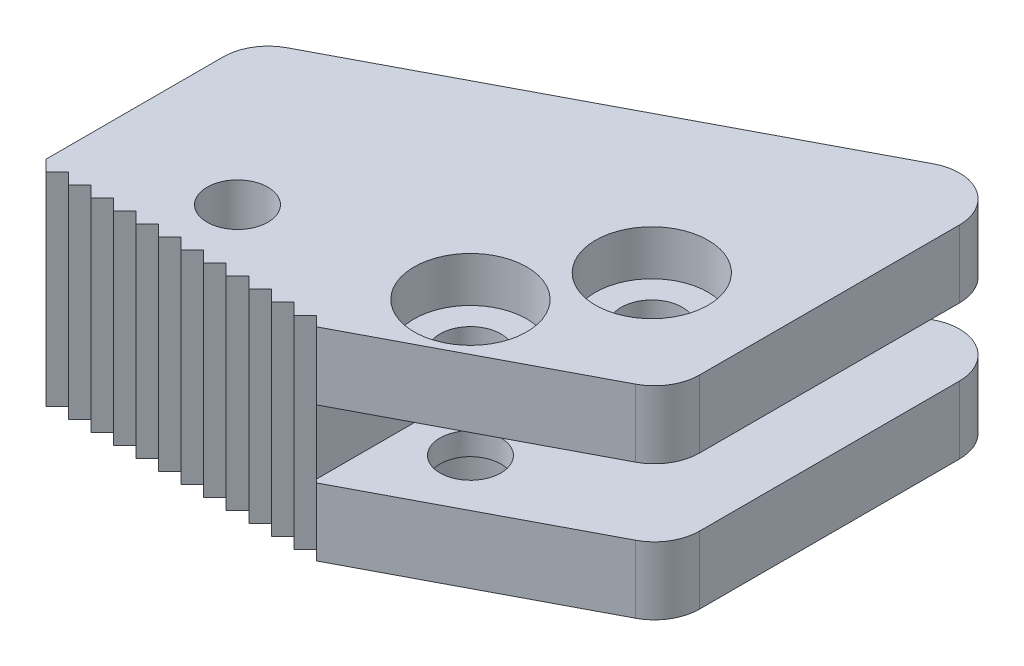
SolidWorks part; units mm, degrees
ref_plane "Alzado" through (0, 0, 0) normal (0, 0, 1) x (1, 0, 0)
ref_plane "Planta" through (0, 0, 0) normal (0, 1, 0) x (1, 0, 0)
ref_plane "Vista lateral" through (0, 0, 0) normal (1, 0, 0) x (0, 0, -1)
sketch "Sketch1" plane through (0, 0, 0) normal (0, 1, 0) x (1, 0, 0)
  line L2 (37.6026, 29.11) -> (37.6026, 11)
  line L3 (37.6026, 11) -> (16.67, 0)
  line L4 (16.67, 0) -> (0, 0)
  line L5 (0, 0) -> (0, 9.35)
  line L6 (0, 9.35) -> (37.6026, 29.11) construction
  line L7 (0, 9.35) -> (0, 15.35)
  line L8 (0, 15.35) -> (37.6026, 35.11)
  line L9 (37.6026, 35.11) -> (37.6026, 29.11)
  dimension "D1" = 9.35
  dimension "D2" = 11
  dimension "D3" = 16.67
  dimension "D4" = 18.11
  dimension "D5" = 6
extrude "Boss-Extrude1" add sketch "Sketch1" along normal blind 18
sketch "Sketch6" plane through (0, 18, 0) normal (0, 1, 0) x (1, 0, 0)
  line L0 (0, 0) -> (-8, 0)
  line L1 (-8, 0) -> (-8, 19.146)
  line L2 (-8, 19.146) -> (37.6026, 43.11)
  line L3 (37.6026, 43.11) -> (37.6026, 35.11)
  line L4 (37.6026, 35.11) -> (0, 15.35)
  line L5 (0, 15.35) -> (0, 0)
  line L6 (37.6026, 11) -> (37.6026, 35.11) construction
  dimension "D1" = 8
  dimension "D2" = 8
extrude "Boss-Extrude2" add sketch "Sketch6" against normal through all
sketch "Sketch2" plane through (0, 18, 0) normal (0, 1, 0) x (1, 0, 0)
  line L1 (-8, 0) -> (16.67, 0) construction
  circle A0 centre (4, 6) radius 2.7
  circle A1 centre (21.62, 9.06) radius 2.7
  circle A2 centre (27.62, 19.16) radius 2.7
  dimension "D1" = 4
  dimension "D3" = 5.4
  dimension "D2" = 6
  dimension "D4" = 6
  dimension "D5" = 10.1
  dimension "D6" = 4.95
  dimension "D7" = 9.06
extrude "Cut-Extrude1" cut sketch "Sketch2" against normal through all contours A0 | A1 | A2
sketch "Sketch3" plane through (0, 0, 0) normal (0, 0, 1) x (1, 0, 0)
  line L5 (37.6026, 18) -> (37.6026, 0) construction
  line L6 (37.6026, 6) -> (16.6026, 6)
  line L7 (37.6026, 6) -> (37.6026, 12)
  line L8 (37.6026, 12) -> (16.6026, 12)
  line L9 (16.6026, 6) -> (16.6026, 12)
  line L10 (37.6026, 6) -> (16.6026, 12) construction
  line L11 (37.6026, 12) -> (16.6026, 6) construction
  line L12 (37.6026, 0) -> (37.6026, 18) construction
  point P4 (27.1026, 9)
  point P12 (37.6026, 9)
  dimension "D1" = 6
  dimension "D2" = 21
extrude "Cut-Extrude2" cut sketch "Sketch3" against normal through all
sketch "Sketch4" plane through (0, 18, 0) normal (0, 1, 0) x (1, 0, 0)
  line L1 (-8, 0) -> (-8, 1)
  line L2 (-5, 0) -> (-4, 1)
  line L4 (-8, 19.146) -> (-8, 0) construction
  line L33 (-8, 1) -> (-7, 0)
  line L35 (-8, 0) -> (16.67, 0) construction
  line L36 (-7, 0) -> (-6, 1)
  line L38 (-4, 1) -> (-3, 0)
  line L39 (-6, 1) -> (-5, 0)
  line L40 (-8, 0) -> (-8, -0.2)
  line L41 (-8, -0.2) -> (16.67, -0.2)
  line L42 (16.67, -0.2) -> (16.67, 0)
  line L43 (-3, 0) -> (-2, 1)
  line L44 (-2, 1) -> (-1, 0)
  line L45 (-1, 0) -> (0, 1)
  line L46 (0, 1) -> (1, 0)
  line L47 (1, 0) -> (2, 1)
  line L48 (2, 1) -> (3, 0)
  line L49 (3, 0) -> (4, 1)
  line L50 (4, 1) -> (5, 0)
  line L51 (5, 0) -> (6, 1)
  line L52 (6, 1) -> (7, 0)
  line L53 (7, 0) -> (8, 1)
  line L54 (8, 1) -> (9, 0)
  line L55 (9, 0) -> (10, 1)
  line L56 (10, 1) -> (11, 0)
  line L57 (11, 0) -> (12, 1)
  line L58 (12, 1) -> (13, 0)
  line L59 (13, 0) -> (14, 1)
  line L60 (14, 1) -> (15, 0)
  line L61 (15, 0) -> (16, 1)
  line L62 (16, 1) -> (16.8863, 0.1137)
  line L63 (16.8863, 0.1137) -> (16.67, 0)
  line L65 (17, 0) -> (18, 1) [skipped]
  line L66 (18, 1) -> (19, 0) [skipped]
  line L67 (16.67, 0) -> (37.6026, 11) construction
  dimension "D1" = 1
  dimension "D2" = 1
  dimension "D3" = 2
  dimension "D5" = 0.2
  dimension "D4" = 13
extrude "Cut-Extrude5" cut sketch "Sketch4" against normal through all
sketch "Sketch5" plane through (0, 0, 0) normal (0, -1, 0) x (1, 0, 0)
  circle A0 centre (21.62, -9.06) radius 5
  circle A1 centre (27.62, -19.16) radius 5
  dimension "D1" = 10
extrude "Cut-Extrude4" cut sketch "Sketch5" against normal blind 4
ref_plane "Plane1" through (0, 9, 0) normal (0, -1, 0) x (-1, 0, 0)
mirror "Mirror1" about plane through (0, 9, 0) normal (0, -1, 0) of "Cut-Extrude4"
fillet "Fillet1" radius 4 4 edges at (37.6026, 3, -11) (37.6026, 3, -43.11) (37.6026, 15, -43.11) (-8, 9, -19.146)
